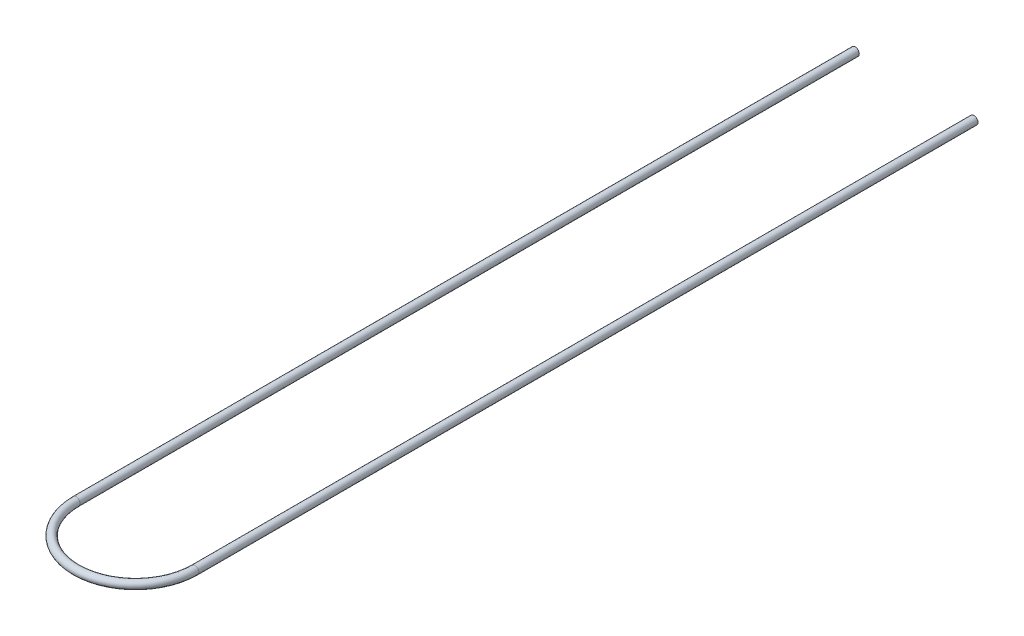
SolidWorks part; units mm, degrees
ref_plane "Front Plane" through (0, 0, 0) normal (0, 0, 1) x (1, 0, 0)
ref_plane "Top Plane" through (0, 0, 0) normal (0, 1, 0) x (1, 0, 0)
ref_plane "Right Plane" through (0, 0, 0) normal (1, 0, 0) x (0, 0, -1)
sketch "Sketch1" plane through (0, 0, 0) normal (0, 1, 0) x (1, 0, 0)
  line L0 (286.16, -300) -> (286.16, -2440)
  line L2 (-40, -300) -> (-40, -2440)
  arc A0 (-40, -2440) -> (286.16, -2440) centre (123.08, -2440) ccw
  dimension "D1" = 2140
  dimension "D2" = 326.16
ref_plane "Plane1" through (286.16, 0, 300) normal (0, 0, -1) x (-1, 0, 0)
sketch "Sketch2" plane through (286.16, 0, 300) normal (0, 0, -1) x (-1, 0, 0)
  circle A0 centre (0, 0) radius 9.95
  circle A1 centre (0, 0) radius 11.1
  dimension "D1" = 22.2
  dimension "D2" = 19.9
sweep "Sweep1" add profiles "Sketch2" path "Sketch1"
